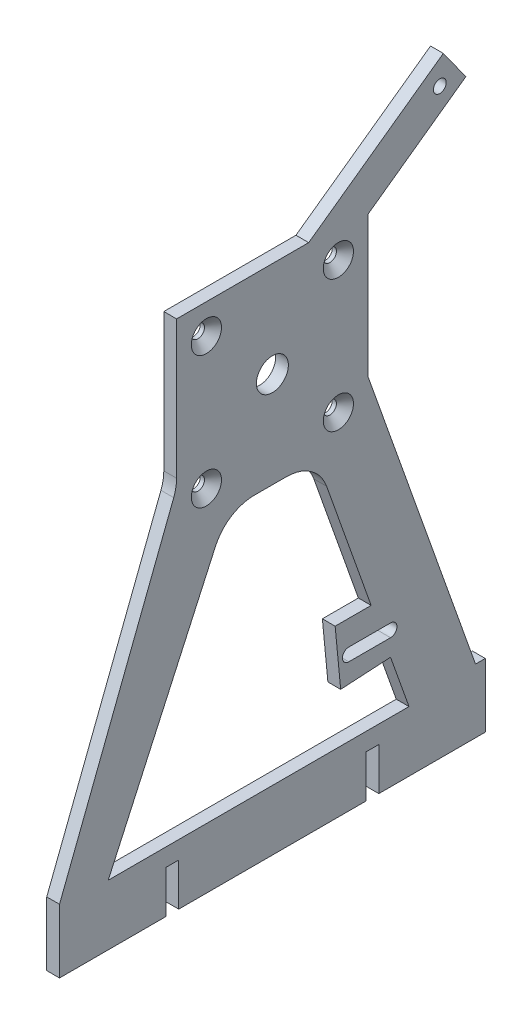
SolidWorks part; units mm, degrees
ref_plane "Front Plane" through (0, 0, 0) normal (0, 0, 1) x (1, 0, 0)
ref_plane "Top Plane" through (0, 0, 0) normal (0, 1, 0) x (1, 0, 0)
ref_plane "Right Plane" through (0, 0, 0) normal (1, 0, 0) x (0, 0, -1)
sketch "Sketch1" plane through (0, 0, 0) normal (1, 0, 0) x (0, 0, -1)
  line L21 (0, 15) -> (27.5, 86.0389)
  line L22 (27.5, 75.3197) -> (72.5, 75.3197)
  line L49 (50, 14.1691) -> (50, 0) construction
  line L50 (50, 14.1691) -> (50, 161.4393) construction
  line L51 (27.5, 75.3197) -> (27.5, 120.3197)
  line L52 (27.5, 120.3197) -> (72.5, 120.3197)
  line L53 (0, 0) -> (25, 0)
  line L54 (0, 0) -> (0, 15)
  line L56 (100, 0) -> (100, 15)
  line L65 (72.5, 75.3197) -> (72.5, 120.3197)
  line L66 (27.5, 75.3197) -> (72.5, 120.3197) construction
  line L67 (27.5, 120.3197) -> (72.5, 75.3197) construction
  line L75 (11.4392, 14.1691) -> (39.2826, 75.3197)
  line L76 (60.3659, 75.3197) -> (73.1989, 39.196)
  line L77 (72.5, 85.9722) -> (97.7129, 15)
  line L80 (97.7129, 15) -> (100, 15)
  line L88 (27.5, 86.0389) -> (39.2826, 75.3197)
  line L89 (60.3659, 75.3197) -> (72.5, 85.9722)
  line L92 (11.4392, 14.1691) -> (50, 14.1691)
  line L93 (50, 14.1691) -> (82.0897, 14.1691)
  line L94 (28, 0) -> (72, 0)
  line L96 (25, 0) -> (25, 10)
  line L97 (25, 10) -> (28, 10)
  line L98 (28, 0) -> (28, 10)
  line L100 (75, 0) -> (75, 10)
  line L101 (75, 10) -> (72, 10)
  line L102 (72, 0) -> (72, 10)
  line L103 (75, 0) -> (100, 0)
  line L104 (27.7379, 49.9649) -> (23.594, 40.8639)
  line L105 (73.1989, 39.196) -> (64.7416, 39.196)
  line L106 (64.7416, 39.196) -> (66.0363, 25.6881)
  line L107 (66.0363, 25.6881) -> (77.7539, 26.3742)
  line L108 (77.7539, 26.3742) -> (82.0897, 14.1691)
  line L109 (58.5277, 120.3197) -> (90.1461, 143.0055)
  line L110 (90.1461, 143.0055) -> (95.4401, 135.6269)
  line L111 (95.4401, 135.6269) -> (68.3836, 116.2143)
  line L112 (68.3836, 116.2143) -> (58.5277, 120.3197)
  line L113 (67.9564, 31.8454) -> (77.7539, 31.8454) construction
  line L114 (67.9564, 33.3454) -> (77.7539, 33.3454)
  line L115 (67.9564, 30.3454) -> (77.7539, 30.3454)
  circle A0 centre (89.32, 136.7444) radius 1.5
  circle A6 centre (34.5, 82.3197) radius 1.55
  circle A7 centre (65.5, 82.3197) radius 1.55
  circle A8 centre (65.5, 113.3197) radius 1.55
  circle A9 centre (34.5, 113.3197) radius 1.55
  arc A11 (67.9564, 33.3454) -> (67.9564, 30.3454) centre (67.9564, 31.8454) ccw
  arc A12 (77.7539, 30.3454) -> (77.7539, 33.3454) centre (77.7539, 31.8454) ccw
  circle A13 centre (50, 97.8197) radius 3.75
  point P2 (50, 97.8197)
  point P43 (72.8551, 31.8454)
  point P57 (89.32, 136.7444)
  dimension "D2" = 3.1
  dimension "D3" = 3
  dimension "D4" = 2
  dimension "D5" = 2
  dimension "D6" = 3
  dimension "D19" = 7.5
  dimension "D10" = 3
  dimension "D8" = 10
  dimension "D7" = 15.5
  dimension "D9" = 15.5
  dimension "D11" = 10
  dimension "D12" = 3
  dimension "D13" = 25
  dimension "D14" = 25
  dimension "D15" = 45
  dimension "D16" = 45
  dimension "D17" = 100
  dimension "D18" = 15
  dimension "D20" = 15
extrude "Boss-Extrude2" add sketch "Sketch1" along normal blind 3
chamfer "Chamfer1" distance 2 angle 45 4 edges at (3, 82.3197, -36.05) (3, 82.3197, -67.05) (3, 113.3197, -67.05) (3, 113.3197, -36.05)
fillet "Fillet2" radius 10 3 edges at (1.5, 75.3197, -60.3659) (1.5, 75.3197, -39.2826) (1.5, 86.0389, -27.5)
